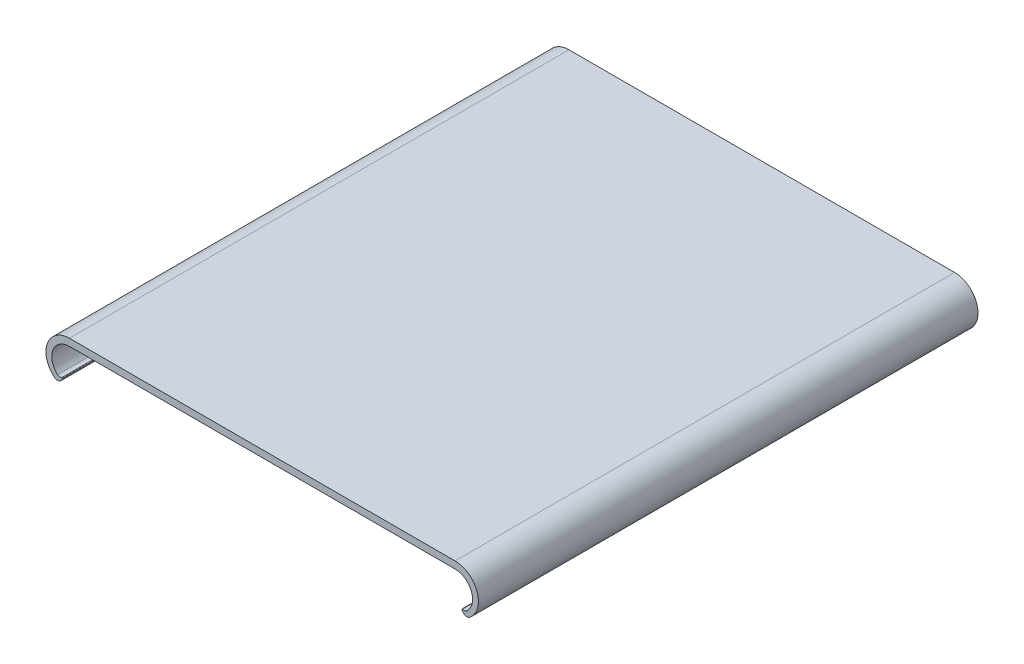
SolidWorks part; units mm, degrees
material "ｱｸﾘﾙ (中-上級の耐衝撃性)"
ref_plane "正面" through (0, 0, 0) normal (0, 0, 1) x (1, 0, 0)
ref_plane "平面" through (0, 0, 0) normal (0, 1, 0) x (1, 0, 0)
ref_plane "右側面" through (0, 0, 0) normal (1, 0, 0) x (0, 0, -1)
sketch "ｽｹｯﾁ1" plane through (0, 0, 0) normal (0, 0, 1) x (1, 0, 0)
  line L0 (0, 24.61) -> (0, -23.9708) construction
  line L1 (33, 0) -> (-33, 0)
  line L2 (33, 0) -> (33, -1.2) construction
  line L4 (33, -1.2) -> (-33, -1.2)
  line L5 (-33, 0) -> (-33, -1.2) construction
  arc A0 (-33, 0) -> (-35.5814, -7.0556) centre (-33, -4) ccw
  arc A1 (-35.5814, -7.0556) -> (-34.1975, -6.5636) centre (-35.0328, -6.4063) ccw
  arc A2 (-35.0328, -6.4063) -> (-34.3172, -6.4801) centre (-34.6256, -5.9642) ccw
  arc A3 (-34.1975, -6.5636) -> (-34.3172, -6.4801) centre (-34.2762, -6.5488) ccw
  arc A4 (-33, -1.2) -> (-35.0328, -6.4063) centre (-33, -4.2) ccw
  arc A5 (33, -1.2) -> (35.0328, -6.4063) centre (33, -4.2) cw
  arc A6 (34.1975, -6.5636) -> (34.3172, -6.4801) centre (34.2762, -6.5488) cw
  arc A7 (35.0328, -6.4063) -> (34.3172, -6.4801) centre (34.6256, -5.9642) cw
  arc A8 (35.5814, -7.0556) -> (34.1975, -6.5636) centre (35.0328, -6.4063) cw
  arc A9 (33, 0) -> (35.5814, -7.0556) centre (33, -4) cw
  point P15 (0, 0)
  point P25 (0, -1.2)
  dimension "D1" = 4
  dimension "D2" = 0.85
  dimension "D3" = 1.2
  dimension "D4" = 37
  dimension "D5" = 3
  dimension "D6" = 0.601
  dimension "D7" = 0.08
extrude "ﾎﾞｽ - 押し出し1" add sketch "ｽｹｯﾁ1" along normal mid plane 85.5
